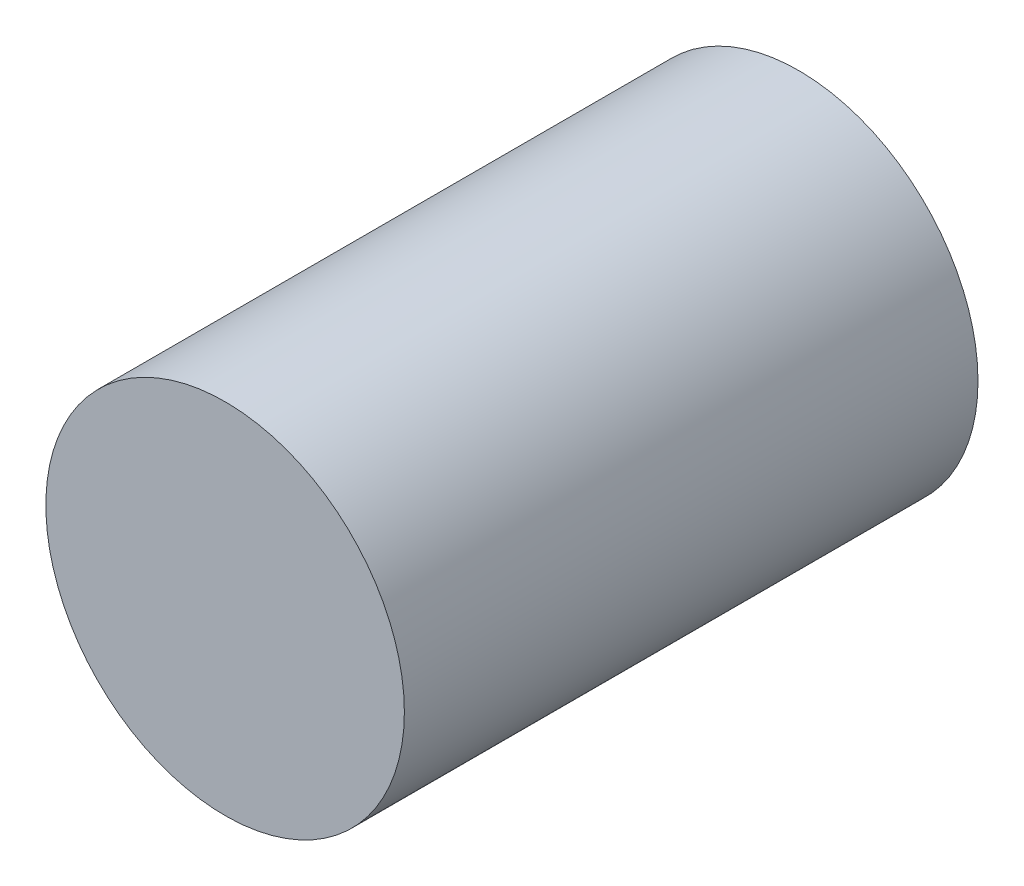
SolidWorks part; units mm, degrees
ref_plane "정면" through (0, 0, 0) normal (0, 0, 1) x (1, 0, 0)
ref_plane "윗면" through (0, 0, 0) normal (0, 1, 0) x (1, 0, 0)
ref_plane "우측면" through (0, 0, 0) normal (1, 0, 0) x (0, 0, -1)
sketch "스케치1" plane through (0, 0, 0) normal (0, 0, 1) x (1, 0, 0)
  circle A0 centre (0, 0) radius 5
  dimension "D1" = 10
extrude "보스-돌출1" add sketch "스케치1" along normal blind 16
